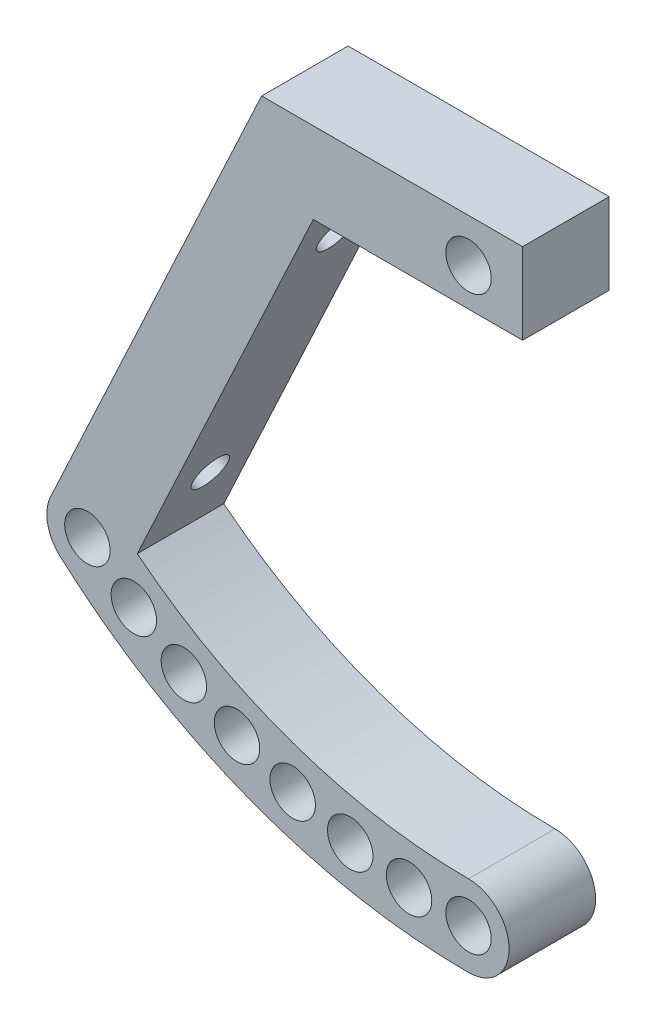
SolidWorks part; units mm, degrees
material "ABS"
ref_plane "Front Plane" through (0, 0, 0) normal (0, 0, 1) x (1, 0, 0)
ref_plane "Top Plane" through (0, 0, 0) normal (0, 1, 0) x (1, 0, 0)
ref_plane "Right Plane" through (0, 0, 0) normal (1, 0, 0) x (0, 0, -1)
sketch "Sketch1" plane through (0, 0, 0) normal (0, 0, 1) x (1, 0, 0)
  line L0 (-26.3199, 30.1475) -> (-21.407, 27.6582) construction
  line L1 (-21.407, 27.6582) -> (-16.2619, 25.6935) construction
  line L2 (-16.2619, 25.6935) -> (-10.9403, 24.2748) construction
  line L3 (-10.9403, 24.2748) -> (-5.5, 23.4173) construction
  line L4 (-5.5, 23.4173) -> (0, 23.1304) construction
  line L5 (-35.2385, 36.5863) -> (-30.9471, 33.1343) construction
  line L6 (-30.9471, 33.1343) -> (-26.3199, 30.1475) construction
  line L7 (5, 72.5) -> (-19.132, 72.5)
  line L8 (5, 72.5) -> (5, 80)
  line L9 (-19.132, 72.5) -> (-19.132, 80)
  line L10 (5, 80) -> (-19.132, 80)
  line L12 (-19.132, 80) -> (-40.2876, 34.6316)
  line L13 (-19.132, 80) -> (-12.3347, 76.8304)
  line L14 (-40.2876, 34.6316) -> (-33.4903, 31.462)
  line L15 (-12.3347, 76.8304) -> (-33.4903, 31.462)
  line L16 (-15.7333, 78.4152) -> (-36.889, 33.0468) construction
  circle A0 centre (0, 76) radius 2.1
  circle A1 centre (0, 23.1304) radius 2.1
  arc A4 (0, 23.1304) -> (-35.2385, 36.5863) centre (0, 76) cw construction
  arc A5 (-37.7379, 33.7907) -> (0, 19.3804) centre (0, 76) ccw
  arc A6 (-32.739, 39.3819) -> (0, 26.8804) centre (0, 76) ccw
  arc A7 (-32.739, 39.3819) -> (-37.7379, 33.7907) centre (-35.2385, 36.5863) ccw
  arc A8 (0, 19.3804) -> (0, 26.8804) centre (0, 23.1304) ccw
  circle A9 centre (-5.5, 23.4173) radius 2.1
  circle A10 centre (-10.9403, 24.2748) radius 2.1
  circle A11 centre (-16.2619, 25.6935) radius 2.1
  circle A12 centre (-21.407, 27.6582) radius 2.1
  circle A13 centre (-26.3199, 30.1475) radius 2.1
  circle A14 centre (-30.9471, 33.1343) radius 2.1
  circle A15 centre (-35.2385, 36.5863) radius 2.1
  point P12 (-18.8601, 26.6088)
  dimension "D1" = 7.5
  dimension "D2" = 5.5
  dimension "D3" = 7.5
  dimension "D4" = 115
extrude "Boss-Extrude1" add sketch "Sketch1" along normal blind 8 contours L13 L15 L7 L8 L10 A0 | L15 L13 L9 L7 | A7 A6 L15 L7 L9 L12 | A14 L15 A6 A7 A5 L14 A15 | A14 L15 L14 A5 A8 A6 A13 A12 A11 A10 A9 A1
sketch "Sketch2" plane through (-46.3567, 21.6165, 0) normal (-0.9063, 0.4226, 0) x (0, 0, 1)
  line L0 (4, 64.4191) -> (4, 18.266) construction
  line L1 (8, 64.4191) -> (0, 64.4191) construction
  line L2 (8, 18.266) -> (0, 18.266) construction
  line L3 (4, 55.0426) -> (0, 64.4191) construction
  line L4 (4, 27.6426) -> (0, 18.266) construction
  circle A0 centre (4, 55.0426) radius 1.65
  circle A1 centre (4, 27.6426) radius 1.65
  dimension "D1" = 3.3
  dimension "D2" = 27.4
extrude "Cut-Extrude1" cut sketch "Sketch2" against normal up to next
